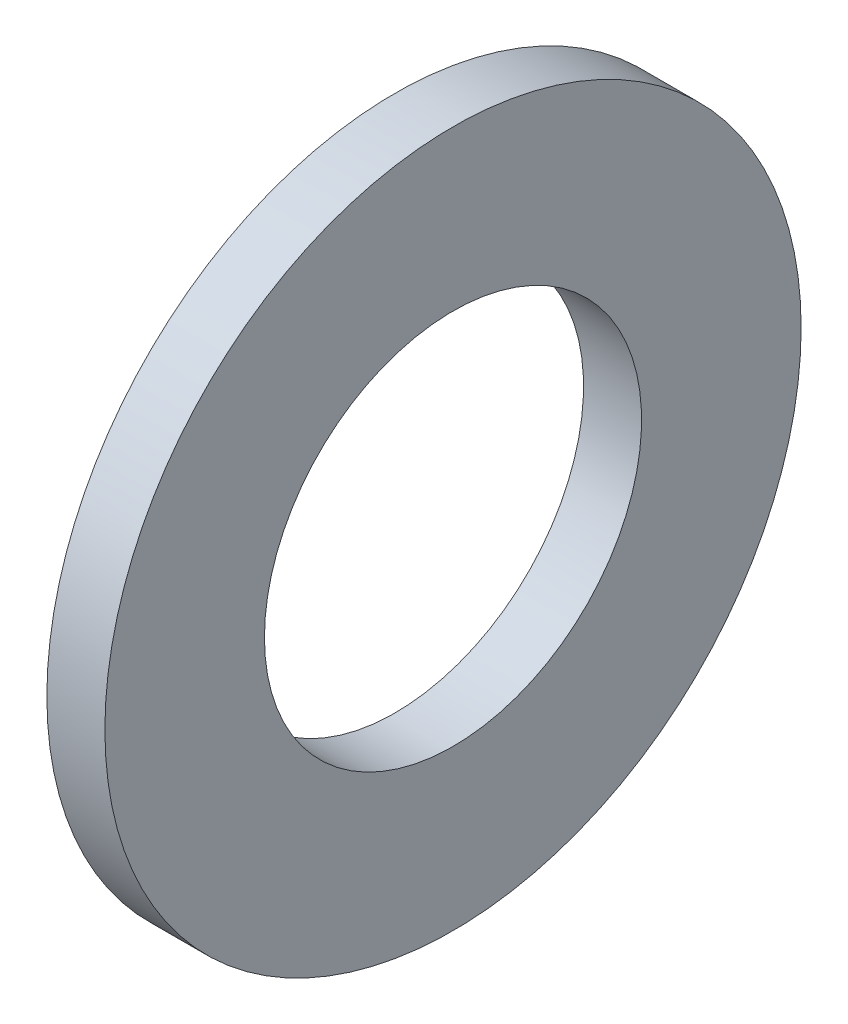
SolidWorks part; units mm, degrees
material "1.0406 (C25)"
ref_plane "Plane1" through (0, 0, 0) normal (0, 0, 1) x (1, 0, 0)
ref_plane "Plane2" through (0, 0, 0) normal (0, 1, 0) x (1, 0, 0)
ref_plane "Plane3" through (0, 0, 0) normal (1, 0, 0) x (0, 0, -1)
sketch "Sketch1" plane through (0, 0, 0) normal (0, 0, 1) x (1, 0, 0)
  line L0 (-34.925, 0) -> (9.525, 0) construction
  line L1 (0, 6.5) -> (0, 12)
  line L2 (0, 12) -> (-2, 12)
  line L3 (-2, 12) -> (-2, 6.5)
  line L4 (-2, 6.5) -> (0, 6.5)
  dimension "Thickness" = 2
  dimension "Inside_dia" = 13
  dimension "Outside_dia" = 24
revolve "Base-Revolve" add sketch "Sketch1" angle 360 about L0
